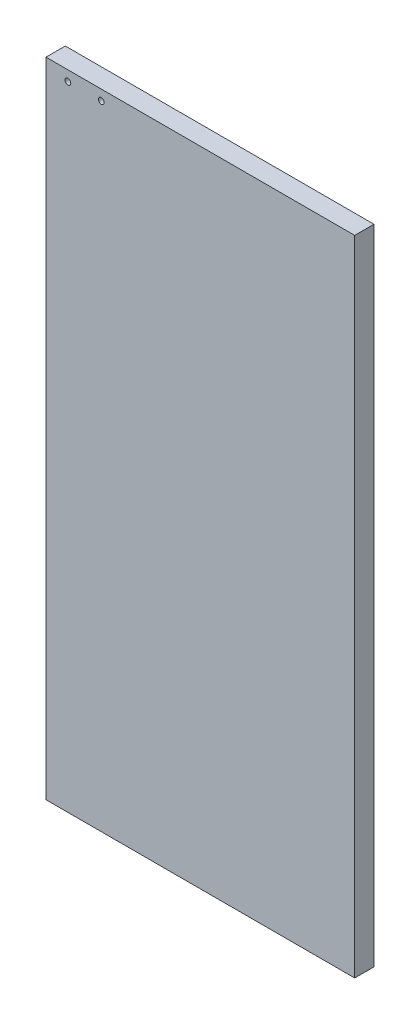
SolidWorks part; units mm, degrees
ref_plane "Plan de face" through (0, 0, 0) normal (0, 0, 1) x (1, 0, 0)
ref_plane "Plan de dessus" through (0, 0, 0) normal (0, 1, 0) x (1, 0, 0)
ref_plane "Plan de droite" through (0, 0, 0) normal (1, 0, 0) x (0, 0, -1)
sketch "Esquisse1" plane through (0, 0, 0) normal (0, 0, 1) x (1, 0, 0)
  line L1 (0, 0) -> (240, 0)
  line L2 (0, 0) -> (0, 500)
  line L3 (0, 500) -> (240, 500)
  line L4 (240, 0) -> (240, 500)
  dimension "D1" = 240
  dimension "D2" = 500
extrude "Boss.-Extru.1" add sketch "Esquisse1" along normal blind 15
sketch "Esquisse2" plane through (0, 0, 15) normal (0, 0, 1) x (1, 0, 0)
  line L0 (0, 492) -> (30, 492) construction
  line L1 (0, 500) -> (0, 0) construction
  line L2 (30, 492) -> (30, 500) construction
  line L3 (240, 500) -> (0, 500) construction
  circle A0 centre (17, 492) radius 2.25
  circle A1 centre (43, 492) radius 2.25
  dimension "D1" = 26
  dimension "D2" = 4.5
  dimension "D3" = 8
  dimension "D4" = 30
extrude "Enlèv. mat.-Extru.1" cut sketch "Esquisse2" against normal through all both and the other way through all
